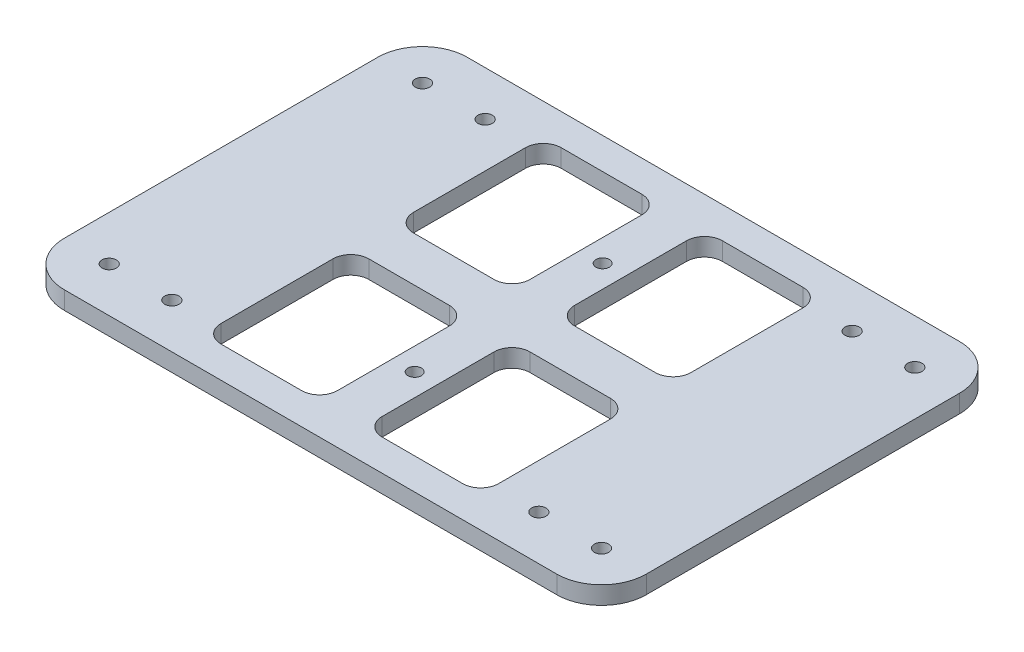
SolidWorks part; units mm, degrees
ref_plane "Front Plane" through (0, 0, 0) normal (0, 0, 1) x (1, 0, 0)
ref_plane "Top Plane" through (0, 0, 0) normal (0, 1, 0) x (1, 0, 0)
ref_plane "Right Plane" through (0, 0, 0) normal (1, 0, 0) x (0, 0, -1)
sketch "Sketch2" plane through (0, 0, 0) normal (0, 1, 0) x (1, 0, 0)
  line L1 (6.2712, 10.565) -> (136.2712, 10.565)
  line L2 (6.2712, 10.565) -> (6.2712, 100.565)
  line L3 (6.2712, 100.565) -> (136.2712, 100.565)
  line L4 (136.2712, 10.565) -> (136.2712, 100.565)
  dimension "D1" = 130
  dimension "D2" = 90
extrude "Boss-Extrude1" add sketch "Sketch2" against normal blind 4
sketch "Sketch3" plane through (0, 0, 0) normal (0, 1, 0) x (1, 0, 0)
  line L0 (71.2712, 100.565) -> (71.2712, 10.565) construction
  line L1 (136.2712, 100.565) -> (6.2712, 100.565) construction
  line L2 (6.2712, 10.565) -> (136.2712, 10.565) construction
  line L3 (6.2712, 55.565) -> (136.2712, 55.565) construction
  line L4 (6.2712, 100.565) -> (6.2712, 10.565) construction
  line L5 (136.2712, 10.565) -> (136.2712, 100.565) construction
  line L7 (112.2712, 63.565) -> (126.2712, 63.565) construction
  line L8 (112.2712, 63.565) -> (112.2712, 47.565) construction
  line L9 (112.2712, 47.565) -> (126.2712, 47.565) construction
  line L10 (126.2712, 63.565) -> (126.2712, 47.565) construction
  circle A0 centre (126.2712, 63.565) radius 1.5
  circle A1 centre (126.2712, 47.565) radius 1.5
  circle A2 centre (112.2712, 47.565) radius 1.5
  circle A3 centre (112.2712, 63.565) radius 1.5
  circle A4 centre (16.2712, 47.565) radius 1.5
  circle A5 centre (30.2712, 47.565) radius 1.5
  circle A6 centre (16.2712, 63.565) radius 1.5
  circle A7 centre (30.2712, 63.565) radius 1.5
  point P16 (112.2712, 55.565)
  dimension "D4" = 3
  dimension "D1" = 14
  dimension "D2" = 16
  dimension "D3" = 10
extrude "Cut-Extrude1" cut sketch "Sketch3" against normal blind 10 contours A6 | A7 | A4 | A5 | A0 | A3 | A2 | A1
sketch "Sketch4" plane through (0, 0, 0) normal (0, 1, 0) x (1, 0, 0)
  line L0 (16.2712, 47.565) -> (16.2712, 10.565) construction
  line L1 (6.2712, 10.565) -> (136.2712, 10.565) construction
  line L2 (30.2712, 47.565) -> (30.2712, 10.565) construction
  line L3 (6.2712, 55.565) -> (136.2712, 55.565) construction
  line L4 (136.2712, 100.565) -> (6.2712, 100.565) construction
  line L5 (6.2712, 100.565) -> (6.2712, 10.565) construction
  line L6 (71.2712, 100.565) -> (71.2712, 10.565) construction
  line L7 (16.2712, 20.565) -> (71.2712, 20.565) construction
  line L8 (136.2712, 10.565) -> (136.2712, 100.565) construction
  circle A0 centre (16.2712, 20.565) radius 1.6
  circle A1 centre (30.2712, 20.565) radius 1.6
  circle A2 centre (30.2712, 90.565) radius 1.6
  circle A3 centre (16.2712, 90.565) radius 1.6
  circle A4 centre (112.2712, 20.565) radius 1.6
  circle A5 centre (126.2712, 20.565) radius 1.6
  circle A6 centre (126.2712, 90.565) radius 1.6
  circle A7 centre (112.2712, 90.565) radius 1.6
  point P23 (30.2712, 20.565)
  dimension "D2" = 3.2
  dimension "D1" = 10
extrude "Cut-Extrude2" cut sketch "Sketch4" against normal blind 10
fillet "Fillet1" radius 10 4 edges at (136.2712, -2, -100.565) (6.2712, -2, -100.565) (6.2712, -2, -10.565) (136.2712, -2, -10.565)
sketch "Sketch5" plane through (0, 0, 0) normal (0, 1, 0) x (1, 0, 0)
  line L0 (71.2712, 100.565) -> (71.2712, 10.565) construction
  line L1 (126.2712, 100.565) -> (16.2712, 100.565) construction
  line L2 (16.2712, 10.565) -> (126.2712, 10.565) construction
  line L3 (6.2712, 55.565) -> (136.2712, 55.565) construction
  line L4 (6.2712, 90.565) -> (6.2712, 20.565) construction
  line L5 (136.2712, 20.565) -> (136.2712, 90.565) construction
  line L6 (76.2712, 89.565) -> (76.2712, 64.565)
  line L7 (80.2712, 60.565) -> (98.2712, 60.565)
  line L9 (80.2712, 93.565) -> (98.2712, 93.565)
  line L10 (102.2712, 89.565) -> (102.2712, 64.565)
  line L11 (40.2712, 89.565) -> (40.2712, 64.565)
  line L12 (62.2712, 93.565) -> (44.2712, 93.565)
  line L13 (62.2712, 60.565) -> (44.2712, 60.565)
  line L14 (66.2712, 89.565) -> (66.2712, 64.565)
  line L15 (66.2712, 21.565) -> (66.2712, 46.565)
  line L16 (62.2712, 50.565) -> (44.2712, 50.565)
  line L17 (62.2712, 17.565) -> (44.2712, 17.565)
  line L18 (40.2712, 21.565) -> (40.2712, 46.565)
  line L19 (102.2712, 21.565) -> (102.2712, 46.565)
  line L20 (80.2712, 17.565) -> (98.2712, 17.565)
  line L21 (80.2712, 50.565) -> (98.2712, 50.565)
  line L22 (76.2712, 21.565) -> (76.2712, 46.565)
  circle A0 centre (112.2712, 90.565) radius 1.6 construction
  arc A1 (102.2712, 89.565) -> (98.2712, 93.565) centre (98.2712, 89.565) ccw
  arc A2 (102.2712, 64.565) -> (98.2712, 60.565) centre (98.2712, 64.565) cw
  arc A3 (80.2712, 60.565) -> (76.2712, 64.565) centre (80.2712, 64.565) cw
  arc A4 (76.2712, 89.565) -> (80.2712, 93.565) centre (80.2712, 89.565) cw
  arc A5 (66.2712, 89.565) -> (62.2712, 93.565) centre (62.2712, 89.565) ccw
  arc A6 (62.2712, 60.565) -> (66.2712, 64.565) centre (62.2712, 64.565) ccw
  arc A7 (40.2712, 64.565) -> (44.2712, 60.565) centre (44.2712, 64.565) ccw
  arc A8 (40.2712, 89.565) -> (44.2712, 93.565) centre (44.2712, 89.565) cw
  arc A9 (40.2712, 21.565) -> (44.2712, 17.565) centre (44.2712, 21.565) ccw
  arc A10 (40.2712, 46.565) -> (44.2712, 50.565) centre (44.2712, 46.565) cw
  arc A11 (62.2712, 50.565) -> (66.2712, 46.565) centre (62.2712, 46.565) cw
  arc A12 (66.2712, 21.565) -> (62.2712, 17.565) centre (62.2712, 21.565) cw
  arc A13 (76.2712, 21.565) -> (80.2712, 17.565) centre (80.2712, 21.565) ccw
  arc A14 (80.2712, 50.565) -> (76.2712, 46.565) centre (80.2712, 46.565) ccw
  arc A15 (102.2712, 46.565) -> (98.2712, 50.565) centre (98.2712, 46.565) ccw
  arc A16 (102.2712, 21.565) -> (98.2712, 17.565) centre (98.2712, 21.565) cw
  dimension "D5" = 4
  dimension "D1" = 5
  dimension "D2" = 5
  dimension "D3" = 10
  dimension "D4" = 7
extrude "Cut-Extrude3" cut sketch "Sketch5" against normal blind 10
sketch "Sketch6" plane through (0, 0, 0) normal (0, 1, 0) x (1, 0, 0)
  circle A0 centre (30.2712, 63.565) radius 1.5
  circle A1 centre (30.2712, 47.565) radius 1.5
  circle A2 centre (16.2712, 47.565) radius 1.5
  circle A3 centre (16.2712, 63.565) radius 1.5
  circle A4 centre (112.2712, 63.565) radius 1.5
  circle A5 centre (126.2712, 63.565) radius 1.5
  circle A6 centre (126.2712, 47.565) radius 1.5
  circle A7 centre (112.2712, 47.565) radius 1.5
extrude "Boss-Extrude2" add sketch "Sketch6" against normal up to surface (4 mm away) up to face at (89.2712, -4, -34.065)
sketch "Sketch7" plane through (0, 0, 0) normal (0, 1, 0) x (1, 0, 0)
  line L0 (71.2712, 100.565) -> (71.2712, 10.565) construction
  line L1 (126.2712, 100.565) -> (16.2712, 100.565) construction
  line L2 (16.2712, 10.565) -> (126.2712, 10.565) construction
  line L3 (6.2712, 55.565) -> (136.2712, 55.565) construction
  line L4 (6.2712, 90.565) -> (6.2712, 20.565) construction
  line L5 (136.2712, 20.565) -> (136.2712, 90.565) construction
  line L7 (33.0212, 24.815) -> (109.5212, 24.815) construction
  line L8 (33.0212, 24.815) -> (33.0212, 86.315) construction
  line L9 (33.0212, 86.315) -> (109.5212, 86.315) construction
  line L10 (109.5212, 24.815) -> (109.5212, 86.315) construction
  circle A0 centre (71.2712, 75.815) radius 1.5
  circle A1 centre (71.2712, 33.815) radius 1.5
  point P16 (71.2712, 86.315)
  point P17 (109.5212, 55.565)
  point P22 (71.2712, 77.315)
  dimension "D3" = 3
  dimension "D4" = 3
  dimension "D6" = 9
  dimension "D1" = 61.5
  dimension "D2" = 76.5
  dimension "D5" = 9
extrude "Cut-Extrude4" cut sketch "Sketch7" against normal blind 10
